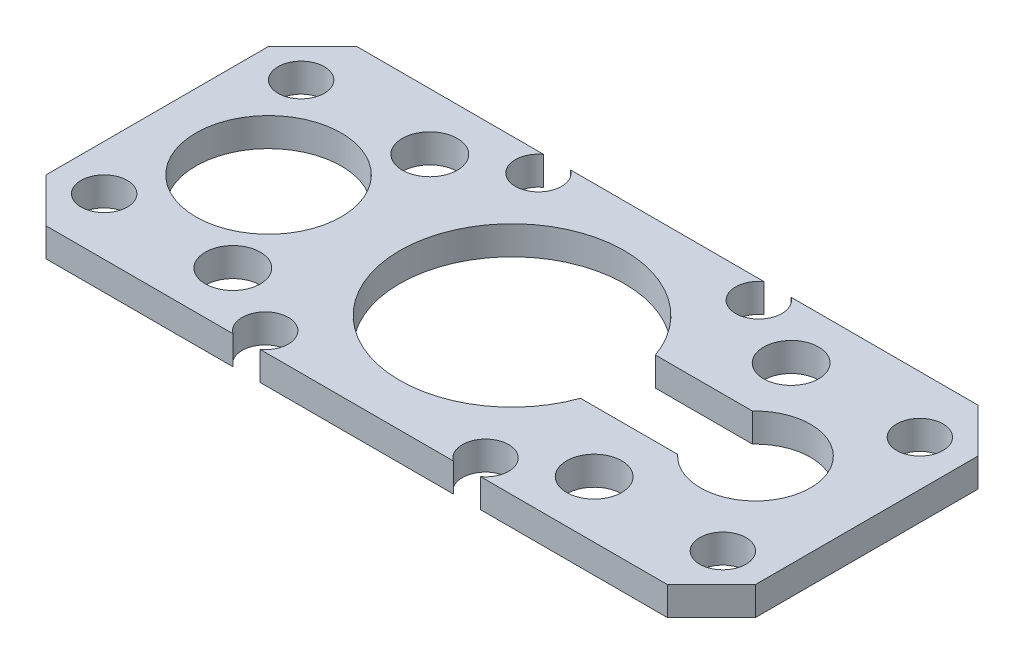
SolidWorks part; units mm, degrees
ref_plane "Front" through (0, 0, 0) normal (0, 0, 1) x (1, 0, 0)
ref_plane "Top" through (0, 0, 0) normal (0, 1, 0) x (1, 0, 0)
ref_plane "Right" through (0, 0, 0) normal (1, 0, 0) x (0, 0, -1)
sketch "Sketch1" plane through (0, 0, 0) normal (0, 1, 0) x (1, 0, 0)
  line L0 (-5.5671, 8.9535) -> (5.5671, 8.9535)
  line L1 (-6.35, -7.874) -> (6.35, -7.874) construction
  line L2 (-6.35, -7.874) -> (-6.35, 7.874) construction
  line L3 (-6.35, 7.874) -> (6.35, 7.874) construction
  line L4 (6.35, -7.874) -> (6.35, 7.874) construction
  line L5 (-6.35, -7.874) -> (6.35, 7.874) construction
  line L6 (-6.35, 7.874) -> (6.35, -7.874) construction
  line L7 (-17.8308, -5.6769) -> (17.8308, -5.6769) construction
  line L8 (-17.8308, -5.6769) -> (-17.8308, 5.6769) construction
  line L9 (-17.8308, 5.6769) -> (17.8308, 5.6769) construction
  line L10 (17.8308, -5.6769) -> (17.8308, 5.6769) construction
  line L11 (-17.8308, -5.6769) -> (17.8308, 5.6769) construction
  line L12 (-17.8308, 5.6769) -> (17.8308, -5.6769) construction
  line L13 (-10.414, -5.6769) -> (10.414, -5.6769) construction
  line L14 (-10.414, -5.6769) -> (-10.414, 5.6769) construction
  line L15 (-10.414, 5.6769) -> (10.414, 5.6769) construction
  line L16 (10.414, -5.6769) -> (10.414, 5.6769) construction
  line L17 (-10.414, -5.6769) -> (10.414, 5.6769) construction
  line L18 (-10.414, 5.6769) -> (10.414, -5.6769) construction
  line L19 (-20.447, -8.9535) -> (-7.1329, -8.9535)
  line L20 (-20.447, -8.9535) -> (-20.447, 8.9535)
  line L21 (-20.447, 8.9535) -> (-7.1329, 8.9535)
  line L22 (20.447, -8.9535) -> (20.447, 8.9535)
  line L23 (-20.447, -8.9535) -> (20.447, 8.9535) construction
  line L24 (-20.447, 8.9535) -> (20.447, -8.9535) construction
  line L25 (7.1329, 8.9535) -> (20.447, 8.9535)
  line L26 (7.1329, -8.9535) -> (20.447, -8.9535)
  line L27 (-5.5671, -8.9535) -> (5.5671, -8.9535)
  circle A0 centre (-17.8308, 5.6769) radius 1.3335
  arc A1 (-7.1329, 8.9535) -> (-5.5671, 8.9535) centre (-6.35, 7.874) ccw
  arc A2 (5.5671, 8.9535) -> (7.1329, 8.9535) centre (6.35, 7.874) ccw
  circle A3 centre (17.8308, 5.6769) radius 1.3335
  circle A4 centre (17.8308, -5.6769) radius 1.3335
  arc A5 (7.1329, -8.9535) -> (5.5671, -8.9535) centre (6.35, -7.874) ccw
  arc A6 (-5.5671, -8.9535) -> (-7.1329, -8.9535) centre (-6.35, -7.874) ccw
  circle A7 centre (-17.8308, -5.6769) radius 1.3335
  circle A8 centre (-10.414, 5.6769) radius 1.5875
  circle A9 centre (10.414, 5.6769) radius 1.5875
  circle A10 centre (10.414, -5.6769) radius 1.5875
  circle A11 centre (-10.414, -5.6769) radius 1.5875
  point P0 (0, 0)
  point P6 (0, 0)
  point P11 (0, 0)
  point P16 (0, 0)
  dimension "D8" = 2.667
  dimension "D9" = 3.175
  dimension "D1" = 12.7
  dimension "D2" = 15.748
  dimension "D3" = 11.3538
  dimension "D4" = 35.6616
  dimension "D5" = 40.894
  dimension "D6" = 17.907
  dimension "D7" = 20.828
extrude "Boss-Extrude1" add sketch "Sketch1" along normal blind 1.651
chamfer "Chamfer1" distance 2.54 angle 45 4 edges at (-20.447, 0.8255, 8.9535) (-20.447, 0.8255, -8.9535) (20.447, 0.8255, -8.9535) (20.447, 0.8255, 8.9535)
sketch "Sketch5" plane through (0, 1.651, 0) normal (0, 1, 0) x (1, 0, 0)
  line L0 (-20.447, 0) -> (20.447, 0) construction
  line L1 (-20.447, 6.4135) -> (-20.447, -6.4135) construction
  line L2 (20.447, -6.4135) -> (20.447, 6.4135) construction
  line L3 (5.5671, 8.9535) -> (-5.5671, 8.9535) construction
  line L4 (-14.0335, -8.9535) -> (14.0335, -8.9535) construction
  line L5 (-14.0335, -8.9535) -> (-14.0335, 8.9535) construction
  line L6 (-14.0335, 8.9535) -> (14.0335, 8.9535) construction
  line L7 (14.0335, -8.9535) -> (14.0335, 8.9535) construction
  line L8 (-14.0335, -8.9535) -> (14.0335, 8.9535) construction
  line L9 (-14.0335, 8.9535) -> (14.0335, -8.9535) construction
  line L11 (6.1066, -2.159) -> (11.7056, -2.159)
  line L13 (6.1066, 2.159) -> (11.7056, 2.159)
  line L15 (6.1066, -2.159) -> (11.7056, 2.159) construction
  line L16 (6.1066, 2.159) -> (11.7056, -2.159) construction
  arc A0 (6.1066, 2.159) -> (6.1066, -2.159) centre (0, 0) ccw
  circle A1 centre (-14.0335, 0) radius 4.191
  arc A2 (11.7056, -2.159) -> (11.7056, 2.159) centre (14.0335, 0) ccw
  point P19 (8.9061, 0)
  dimension "D1" = 12.954
  dimension "D3" = 6.35
  dimension "D4" = 8.382
  dimension "D2" = 28.067
  dimension "D5" = 4.318
extrude "Cut-Extrude5" cut sketch "Sketch5" against normal through all
